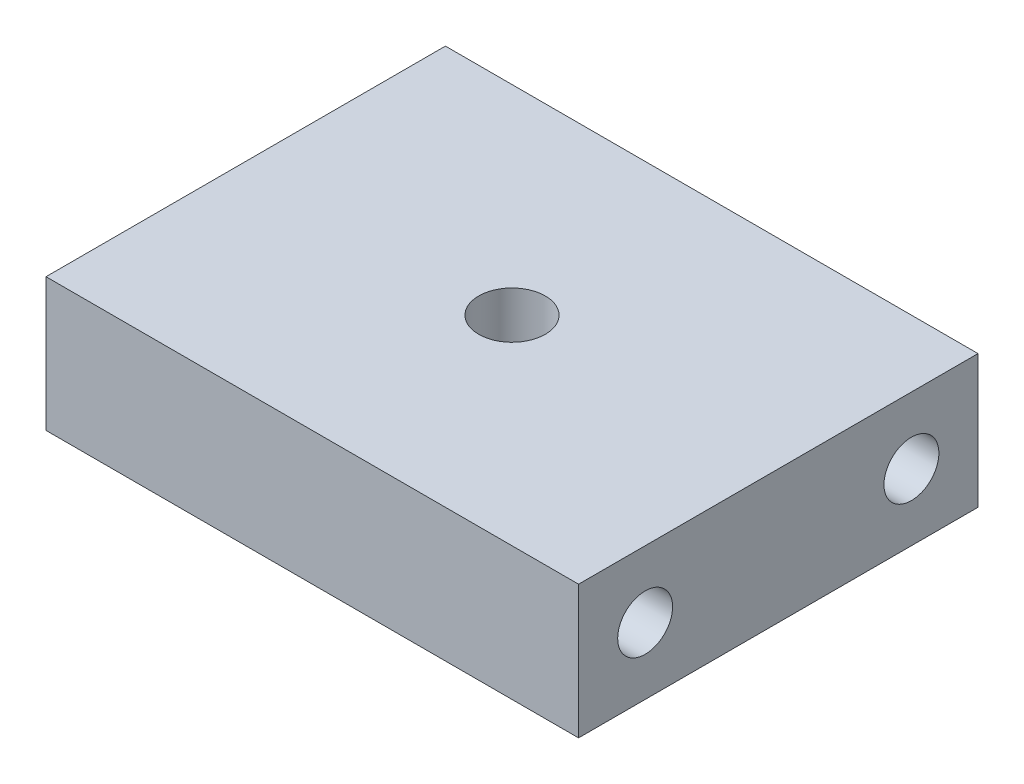
SolidWorks part; units mm, degrees
ref_plane "Plan de face" through (0, 0, 0) normal (0, 0, 1) x (1, 0, 0)
ref_plane "Plan de dessus" through (0, 0, 0) normal (0, 1, 0) x (1, 0, 0)
ref_plane "Plan de droite" through (0, 0, 0) normal (1, 0, 0) x (0, 0, -1)
sketch "Esquisse1" plane through (0, 0, 0) normal (0, 1, 0) x (1, 0, 0)
  line L1 (19.1264, -10.7586) -> (-12.8736, -10.7586)
  line L2 (19.1264, -10.7586) -> (19.1264, 13.2414)
  line L3 (19.1264, 13.2414) -> (-12.8736, 13.2414)
  line L4 (-12.8736, -10.7586) -> (-12.8736, 13.2414)
  dimension "D1" = 32
  dimension "D2" = 24
extrude "Boss.-Extru.1" add sketch "Esquisse1" along normal blind 8
sketch "Esquisse2" plane through (0, 8, 0) normal (0, 1, 0) x (1, 0, 0)
  line L0 (19.1264, -10.7586) -> (19.1264, 13.2414) construction
  line L1 (-12.8736, -10.7586) -> (19.1264, -10.7586) construction
  circle A0 centre (3.1264, 1.2414) radius 2
  dimension "D1" = 4
  dimension "D2" = 16
  dimension "D3" = 12
extrude "Enlèv. mat.-Extru.1" cut sketch "Esquisse2" against normal blind 8
sketch "Esquisse3" plane through (-12.8736, 0, 0) normal (-1, 0, 0) x (0, 0, 1)
  line L1 (-13.2414, 8) -> (10.7586, 8) construction
  line L2 (-13.2414, 8) -> (-13.2414, 0) construction
  circle A0 centre (-9.2414, 4) radius 1.65
  dimension "D1" = 3.3
  dimension "D2" = 4
  dimension "D3" = 4
extrude "Enlèv. mat.-Extru.2" cut sketch "Esquisse3" against normal up to next
sketch "Esquisse4" plane through (-12.8736, 0, 0) normal (-1, 0, 0) x (0, 0, 1)
  line L0 (10.7586, 8) -> (10.7586, 0) construction
  line L1 (-13.2414, 0) -> (10.7586, 0) construction
  circle A0 centre (6.7586, 4) radius 1.65
  dimension "D1" = 3.3
  dimension "D2" = 4
  dimension "D3" = 4
extrude "Enlèv. mat.-Extru.3" cut sketch "Esquisse4" against normal up to next
